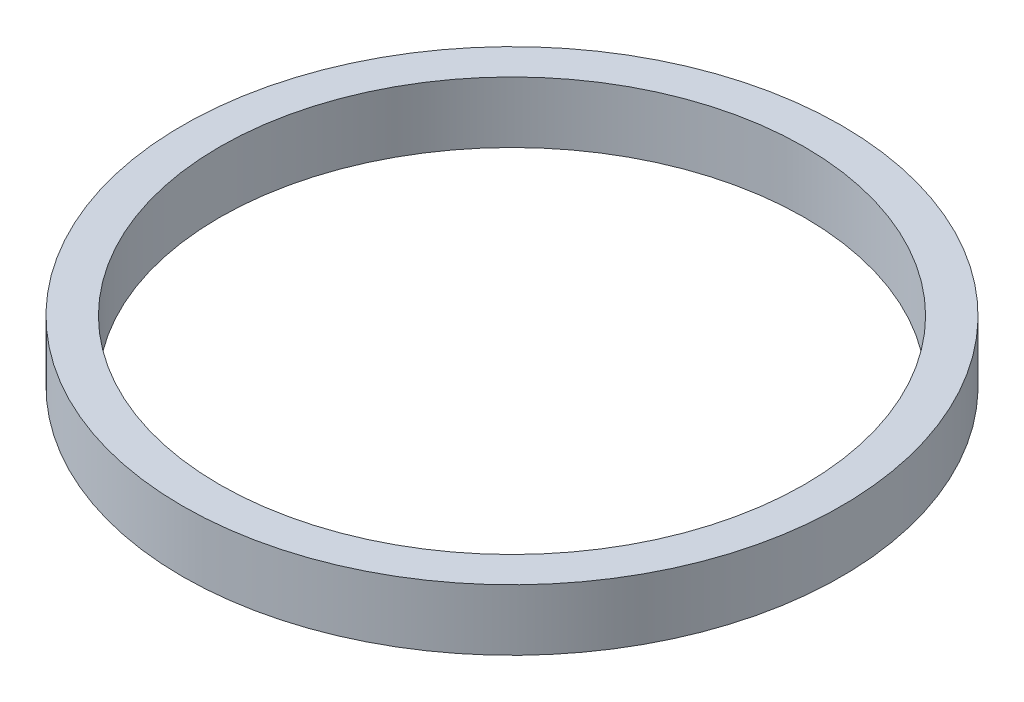
SolidWorks part; units mm, degrees
ref_plane "Plano frontal" through (0, 0, 0) normal (0, 0, 1) x (1, 0, 0)
ref_plane "Plano superior" through (0, 0, 0) normal (0, 1, 0) x (1, 0, 0)
ref_plane "Plano direito" through (0, 0, 0) normal (1, 0, 0) x (0, 0, -1)
sketch "Esboço1" plane through (0, 0, 0) normal (0, 1, 0) x (1, 0, 0)
  circle A0 centre (0, 0) radius 37.75
  circle A2 centre (0, 0) radius 33.5 construction
  circle A3 centre (0, 0) radius 33.5
  dimension "D1" = 75.5
extrude "Ressalto-extrusão1" add sketch "Esboço1" along normal blind 7
